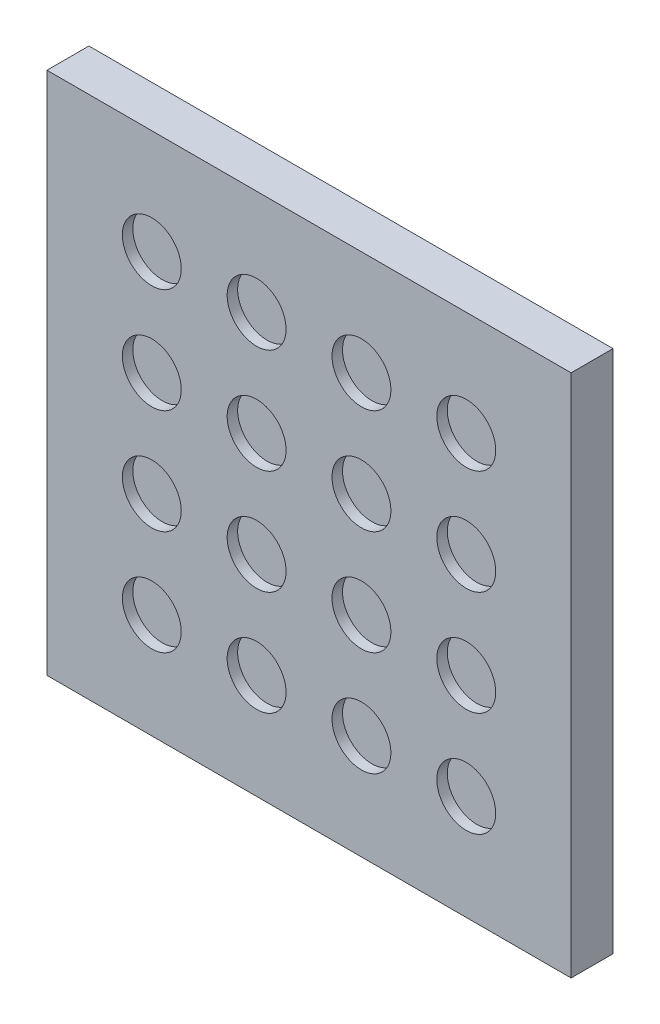
SolidWorks part; units mm, degrees
ref_plane "Front Plane" through (0, 0, 0) normal (0, 0, 1) x (1, 0, 0)
ref_plane "Top Plane" through (0, 0, 0) normal (0, 1, 0) x (1, 0, 0)
ref_plane "Right Plane" through (0, 0, 0) normal (1, 0, 0) x (0, 0, -1)
sketch "Sketch1" plane through (0, 0, 0) normal (0, 0, 1) x (1, 0, 0)
  line L1 (-10, 10) -> (40, 10)
  line L2 (-10, 10) -> (-10, -40)
  line L3 (-10, -40) -> (40, -40)
  line L4 (40, 10) -> (40, -40)
  circle A0 centre (0, 0) radius 2.81
  circle A1 centre (10, 0) radius 2.81
  circle A2 centre (20, 0) radius 2.81
  circle A3 centre (30, 0) radius 2.81
  circle A4 centre (10, -10) radius 2.81
  circle A5 centre (20, -10) radius 2.81
  circle A6 centre (30, -10) radius 2.81
  circle A7 centre (10, -20) radius 2.81
  circle A8 centre (20, -20) radius 2.81
  circle A9 centre (30, -20) radius 2.81
  circle A10 centre (10, -30) radius 2.81
  circle A11 centre (20, -30) radius 2.81
  circle A12 centre (30, -30) radius 2.81
  circle A13 centre (0, -10) radius 2.81
  circle A14 centre (0, -20) radius 2.81
  circle A15 centre (0, -30) radius 2.81
  point P37 (0, 0)
  point P38 (0, 0)
  dimension "D1" = 5.62
  dimension "D7" = 10
  dimension "D4" = 10
  dimension "D5" = 10
  dimension "D6" = 10
  dimension "D8" = 10
  dimension "D2" = 4
  dimension "D3" = 4
extrude "Boss-Extrude1" add sketch "Sketch1" along normal blind 1
sketch "Sketch2" plane through (0, 0, 0) normal (0, 0, -1) x (-1, 0, 0)
  line L1 (10, 10) -> (-40, 10)
  line L2 (10, 10) -> (10, -40)
  line L3 (10, -40) -> (-40, -40)
  line L4 (-40, 10) -> (-40, -40)
extrude "Boss-Extrude2" add sketch "Sketch2" along normal blind 3
